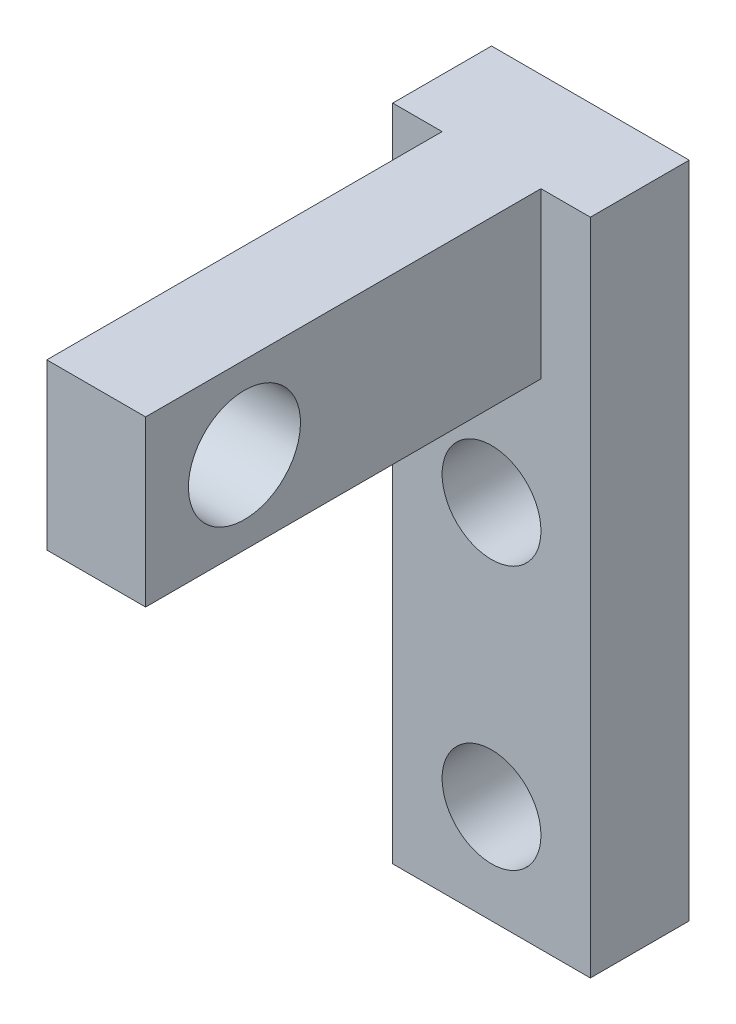
SolidWorks part; units mm, degrees
ref_plane "Front Plane" through (0, 0, 0) normal (0, 0, 1) x (1, 0, 0)
ref_plane "Top Plane" through (0, 0, 0) normal (0, 1, 0) x (1, 0, 0)
ref_plane "Right Plane" through (0, 0, 0) normal (1, 0, 0) x (0, 0, -1)
sketch "Sketch4" plane through (0, 0, 0) normal (0, 0, 1) x (1, 0, 0)
  line L0 (0, 0) -> (0, 7398.1961) construction
  line L1 (0, 6) -> (50000, 6) construction
  line L3 (-3, -11) -> (3, -11)
  line L4 (-3, -11) -> (-3, 9)
  line L5 (-3, 9) -> (3, 9)
  line L6 (3, -11) -> (3, 9)
  circle A0 centre (0, 0) radius 1.5
  circle A1 centre (0, -8) radius 1.5
  dimension "D1" = 3
  dimension "D2" = 3
  dimension "D3" = 8
  dimension "D4" = 6
  dimension "D5" = 3
  dimension "D6" = 3
  dimension "D7" = 6
  dimension "D8" = 3
extrude "Boss-Extrude1" add sketch "Sketch4" along normal blind 3
sketch "Sketch6" plane through (0, 0, 3) normal (0, 0, 1) x (1, 0, 0)
  line L0 (3, 9) -> (-3, 9) construction
  line L1 (1.5, 9) -> (-1.5, 9)
  line L2 (1.5, 9) -> (1.5, 4)
  line L3 (1.5, 4) -> (-1.5, 4)
  line L4 (-1.5, 9) -> (-1.5, 4)
  dimension "D1" = 3
  dimension "D2" = 1.5
  dimension "D3" = 5
extrude "Boss-Extrude2" add sketch "Sketch6" along normal blind 12
sketch "Sketch7" plane through (1.5, 0, 0) normal (1, 0, 0) x (0, 0, -1)
  line L0 (-15, 6.5) -> (-3, 6.5) construction
  line L1 (-15, 4) -> (-15, 9) construction
  line L2 (-3, 4) -> (-3, 9) construction
  circle A0 centre (-12, 6.5) radius 1.7
  dimension "D1" = 3.4
  dimension "D2" = 3
extrude "Cut-Extrude1" cut sketch "Sketch7" against normal through all
